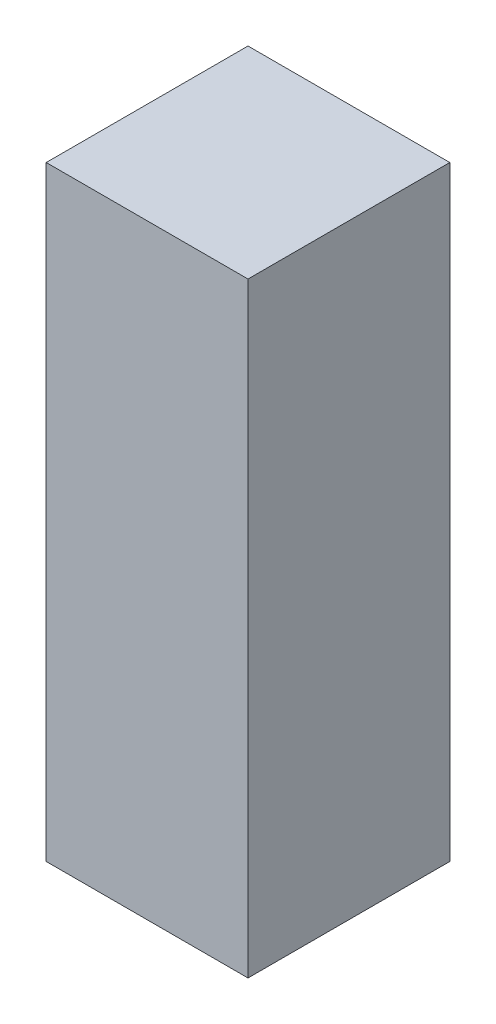
SolidWorks part; units mm, degrees
ref_plane "Front Plane" through (0, 0, 0) normal (0, 0, 1) x (1, 0, 0)
ref_plane "Top Plane" through (0, 0, 0) normal (0, 1, 0) x (1, 0, 0)
ref_plane "Right Plane" through (0, 0, 0) normal (1, 0, 0) x (0, 0, -1)
sketch "Sketch1" plane through (0, 0, 0) normal (0, 1, 0) x (1, 0, 0)
  line L1 (-50.8, 50.8) -> (50.8, 50.8)
  line L2 (-50.8, 50.8) -> (-50.8, -50.8)
  line L3 (-50.8, -50.8) -> (50.8, -50.8)
  line L4 (50.8, 50.8) -> (50.8, -50.8)
  line L5 (-50.8, 50.8) -> (50.8, -50.8) construction
  line L6 (-50.8, -50.8) -> (50.8, 50.8) construction
  point P0 (0, 0)
extrude "Boss-Extrude1" add sketch "Sketch1" along normal blind 304.8
